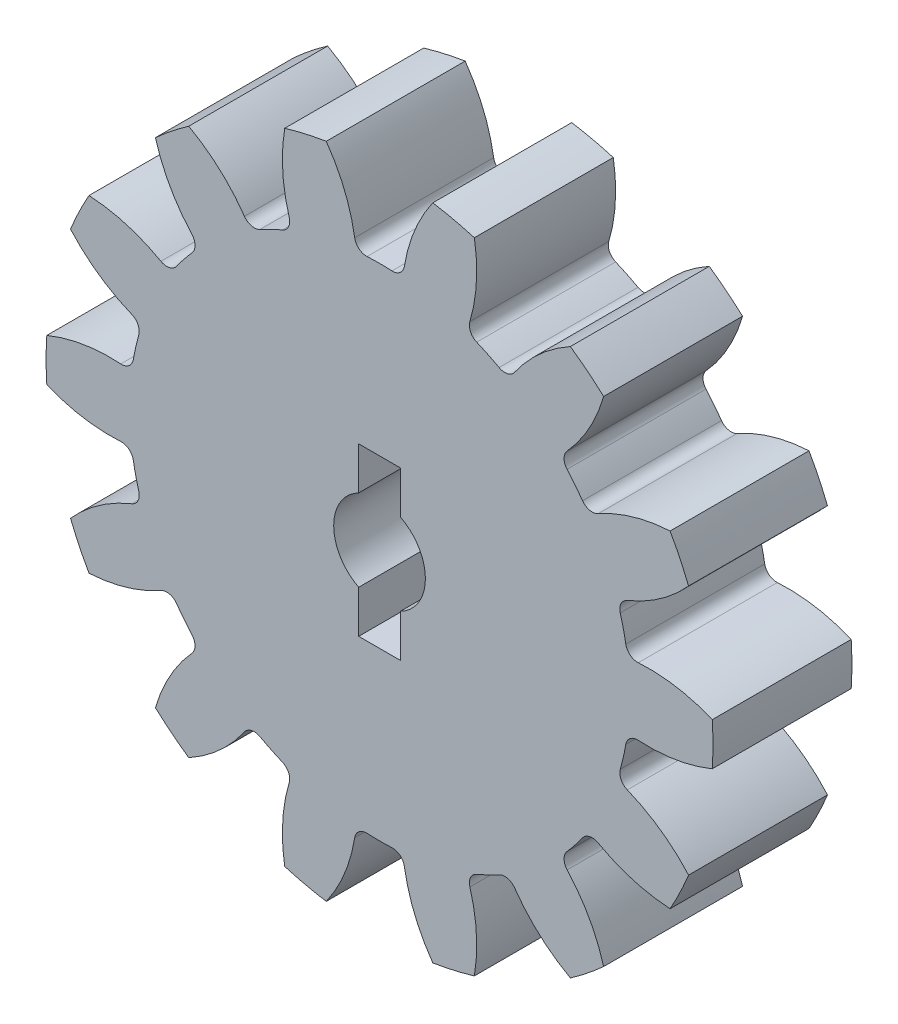
SolidWorks part; units mm, degrees
ref_plane "Front" through (0, 0, 0) normal (0, 0, 1) x (1, 0, 0)
ref_plane "Top" through (0, 0, 0) normal (0, 1, 0) x (1, 0, 0)
ref_plane "Right" through (0, 0, 0) normal (1, 0, 0) x (0, 0, -1)
sketch "Sketch1" plane through (0, 0, 0) normal (0, 0, 1) x (1, 0, 0)
  circle A0 centre (0, 0) radius 9
  circle A1 centre (0, 0) radius 12
  circle A2 centre (0, 0) radius 10.5
  dimension "D1" = 24
  dimension "D2" = 18
  dimension "D3" = 21
extrude "Boss-Extrude1" add sketch "Sketch1" along normal mid plane 5 contours A1
sketch "Sketch3" plane through (0, 0, 0) normal (0, 0, 1) x (1, 0, 0)
  line L0 (0, 0) -> (0, 12) construction
  line L1 (0, 0) -> (-0.8438, 8.9604) construction
  line L2 (-1.1756, 10.434) -> (1.1756, 10.434) construction
  line L3 (-1.7015, 11.8788) -> (0, 7.204) construction
  line L4 (1.1756, 10.434) -> (3.4679, 9.9108) construction
  line L5 (2.6703, 11.6991) -> (0, 0) construction
  arc A0 (-0.8438, 8.9604) -> (0.8438, 8.9604) centre (0, 0) cw
  arc A4 (1.9175, 11.8458) -> (-1.9175, 11.8458) centre (0, 0) ccw
  circle A5 centre (0, 0) radius 12 construction
  arc A7 (-1.9175, 11.8458) -> (-0.8438, 8.9604) centre (-6.7534, 8.4038) cw
  arc A10 (1.9175, 11.8458) -> (0.8438, 8.9604) centre (6.7534, 8.4038) ccw
  circle A11 centre (0, 0) radius 9 construction
  circle A12 centre (0, 0) radius 10.5 construction
  dimension "D1" = 20
  dimension "D2" = 12.857
extrude "Cut-Extrude1" cut sketch "Sketch3" against normal through all both and the other way through all contours A10 A4 A7 A0
fillet "Fillet2" radius 0.43 2 edges at (-0.8438, 8.9604, 0) (0.8438, 8.9604, 0)
pattern_circular "CirPattern1" count 14 over 360 about axis through (0, 0, 0) along (0, 0, 1) of "Cut-Extrude1", "Fillet2"
sketch "Sketch4" plane through (0, 0, 0) normal (0, 0, 1) x (1, 0, 0)
  line L0 (-0.75, 3) -> (0.75, 3)
  line L1 (-0.75, -3) -> (0.75, -3) construction
  line L3 (-0.75, 3) -> (0.75, 3) construction
  line L7 (0.75, 3) -> (0.75, 1.4697)
  line L8 (-0.75, 3) -> (-0.75, 1.4697)
  line L9 (-0.75, -1.4697) -> (-0.75, -3)
  line L10 (-0.75, -3) -> (0.75, -3)
  line L11 (0.75, -3) -> (0.75, -1.4697)
  arc A1 (-0.75, 1.4697) -> (-0.75, -1.4697) centre (0, 0) ccw
  arc A2 (0.75, 1.4697) -> (0.75, -1.4697) centre (0, 0) cw
  dimension "D1" = 1.65
  dimension "D4" = 1.65
  dimension "D2" = 6
  dimension "D3" = 1.5
  dimension "D5" = 1.5
  dimension "D6" = 1.5303
extrude "Through_Center_Hole" cut sketch "Sketch4" against normal through all both and the other way through all
sketch "Sketch5" plane through (0, 0, 2.5) normal (0, 0, 1) x (1, 0, 0)
  circle A0 centre (0, 0) radius 1.65
  dimension "D1" = 3.3
equation "\"od\" = 24'outside diameter"
equation "\"n\"= 14'number of teeth"
equation "\"m\"= \"od\" / ( \"n\" + 2 )'module"
equation "\"p\"= \"m\" * pi'pitch"
equation "\"d\"= \"m\" * \"n\"'primitive diameter"
equation "\"da\"= \"d\" + 2 * \"m\"'head diamater"
equation "\"df\"= \"d\" - 2 * \"m\"'foot diameter"
equation "\"D1@Sketch1\"=\"od\""
equation "\"D2@Sketch1\"=\"df\""
equation "\"D3@Sketch1\"=\"d\""
equation "\"D2@Sketch3\"=180/\"n\""
equation "\"D1@CirPattern1\"=\"n\""
